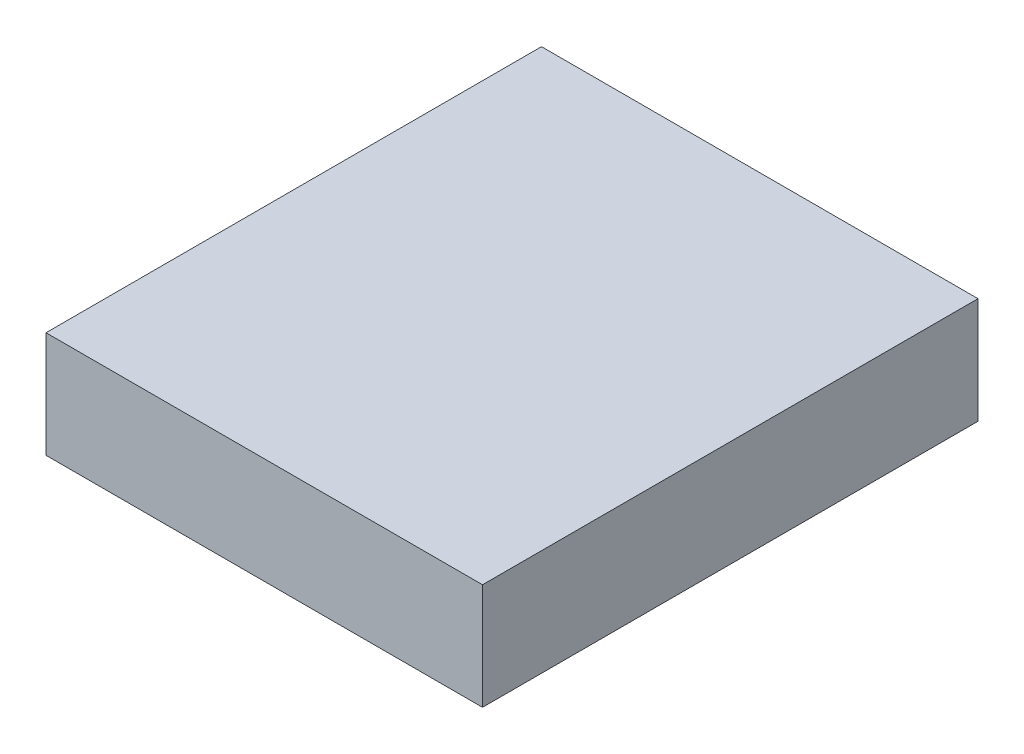
SolidWorks part; units mm, degrees
material "1060 Alloy"
ref_plane "Front Plane" through (0, 0, 0) normal (0, 0, 1) x (1, 0, 0)
ref_plane "Top Plane" through (0, 0, 0) normal (0, 1, 0) x (1, 0, 0)
ref_plane "Right Plane" through (0, 0, 0) normal (1, 0, 0) x (0, 0, -1)
sketch "Sketch1" plane through (0, 0, 0) normal (0, 1, 0) x (1, 0, 0)
  line L1 (-18.5, -21) -> (18.5, -21)
  line L2 (-18.5, -21) -> (-18.5, 21)
  line L3 (-18.5, 21) -> (18.5, 21)
  line L4 (18.5, -21) -> (18.5, 21)
  line L5 (-18.5, -21) -> (18.5, 21) construction
  line L6 (-18.5, 21) -> (18.5, -21) construction
  point P0 (0, 0)
  dimension "D1" = 42
  dimension "D2" = 37
extrude "Boss-Extrude1" add sketch "Sketch1" along normal blind 9
